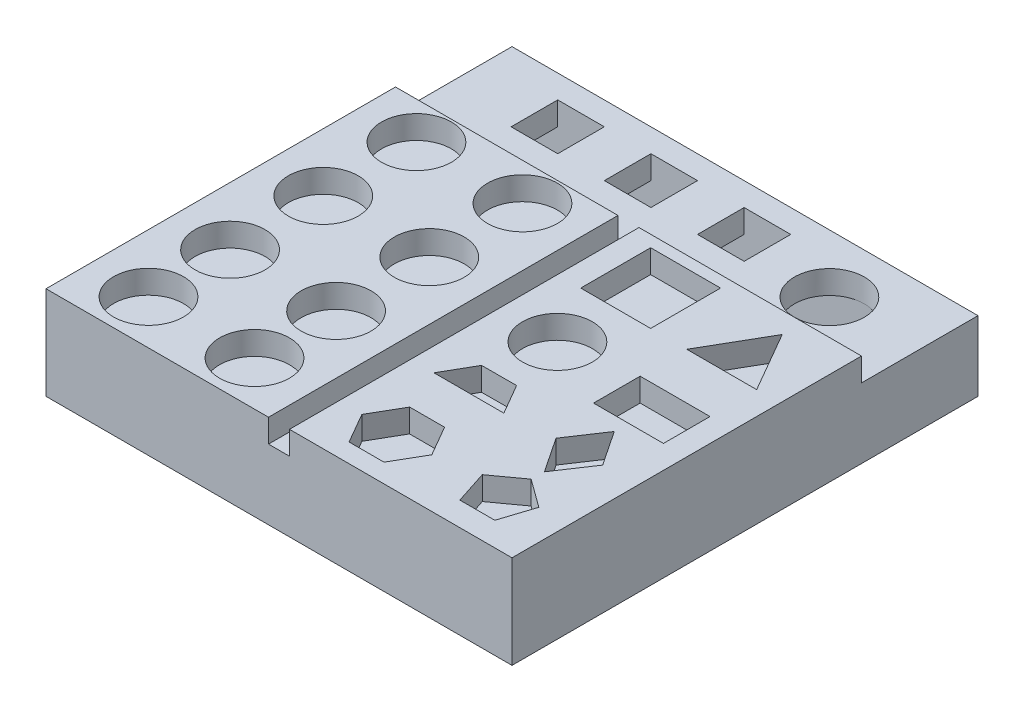
SolidWorks part; units mm, degrees
ref_plane "Alzado" through (0, 0, 0) normal (0, 0, 1) x (1, 0, 0)
ref_plane "Planta" through (0, 0, 0) normal (0, 1, 0) x (1, 0, 0)
ref_plane "Vista lateral" through (0, 0, 0) normal (1, 0, 0) x (0, 0, -1)
sketch "Croquis1" plane through (0, 0, 0) normal (0, 1, 0) x (1, 0, 0)
  line L1 (-200, 200) -> (0, 200)
  line L2 (-200, 200) -> (-200, 0)
  line L3 (-200, 0) -> (0, 0)
  line L4 (0, 200) -> (0, 0)
  dimension "D1" = 200
  dimension "D2" = 200
extrude "Saliente-Extruir1" add sketch "Croquis1" along normal blind 10 contours L2 L1 L4 L3
sketch "Croquis2" plane through (0, 10, 0) normal (0, 1, 0) x (1, 0, 0)
  line L0 (-200, 0) -> (0, 0) construction
  line L1 (-95.5, 0) -> (0, 0)
  line L2 (-95.5, 0) -> (-95.5, 150)
  line L3 (-95.5, 150) -> (0, 150)
  line L4 (0, 0) -> (0, 150)
  line L5 (0, 200) -> (0, 0) construction
  line L6 (-200, 200) -> (-200, 0) construction
  line L7 (-200, 150) -> (-104.5, 150)
  line L8 (-200, 150) -> (-200, 0)
  line L9 (-200, 0) -> (-104.5, 0)
  line L10 (-104.5, 150) -> (-104.5, 0)
  dimension "D1" = 95.5
  dimension "D2" = 150
  dimension "D3" = 95.5
  dimension "D4" = 150
extrude "Saliente-Extruir2" add sketch "Croquis2" along normal blind 10
sketch "Croquis3" plane through (0, 10, 0) normal (0, 1, 0) x (1, 0, 0)
  line L0 (-200, 200) -> (0, 200) construction
  line L1 (-170.376, 190) -> (-150.376, 190)
  line L2 (-170.376, 190) -> (-170.376, 170)
  line L3 (-170.376, 170) -> (-150.376, 170)
  line L4 (-150.376, 190) -> (-150.376, 170)
  line L5 (-170.376, 190) -> (-150.376, 170) construction
  line L6 (-170.376, 170) -> (-150.376, 190) construction
  line L7 (-130.376, 190) -> (-110.376, 190)
  line L8 (-130.376, 190) -> (-130.376, 170)
  line L9 (-130.376, 170) -> (-110.376, 170)
  line L10 (-110.376, 190) -> (-110.376, 170)
  line L11 (-130.376, 190) -> (-110.376, 170) construction
  line L12 (-130.376, 170) -> (-110.376, 190) construction
  line L13 (-90.376, 190) -> (-70.376, 190)
  line L14 (-90.376, 190) -> (-90.376, 170)
  line L15 (-90.376, 170) -> (-70.376, 170)
  line L16 (-70.376, 190) -> (-70.376, 170)
  line L17 (-90.376, 190) -> (-70.376, 170) construction
  line L18 (-90.376, 170) -> (-70.376, 190) construction
  circle A0 centre (-38.7808, 175) radius 15
  point P2 (-160.376, 180)
  point P7 (-120.376, 180)
  point P12 (-80.376, 180)
  dimension "D1" = 30
  dimension "D2" = 20
  dimension "D3" = 20
  dimension "D4" = 20
  dimension "D5" = 20
  dimension "D6" = 20
  dimension "D7" = 20
  dimension "D8" = 10
  dimension "D9" = 10
  dimension "D10" = 10
  dimension "D11" = 20
  dimension "D12" = 20
extrude "Cortar-Extruir1" cut sketch "Croquis3" against normal through all
sketch "Croquis4" plane through (0, 0, 0) normal (0, -1, 0) x (-1, 0, 0)
  line L0 (200, 200) -> (0, 200) construction
  line L1 (200, 0) -> (190, 0)
  line L2 (200, 0) -> (200, 200)
  line L3 (200, 200) -> (190, 200)
  line L4 (190, 0) -> (190, 200)
  line L5 (0, 200) -> (0, 0) construction
  line L6 (200, 200) -> (0, 200)
  line L7 (200, 200) -> (200, 190)
  line L8 (200, 190) -> (0, 190)
  line L9 (0, 200) -> (0, 190)
  line L10 (200, 0) -> (0, 0) construction
  line L11 (0, 200) -> (10, 200)
  line L12 (0, 200) -> (0, 0)
  line L13 (0, 0) -> (10, 0)
  line L14 (10, 200) -> (10, 0)
  line L16 (0, 0) -> (200, 0)
  line L17 (0, 0) -> (0, 10)
  line L18 (0, 10) -> (200, 10)
  line L19 (200, 0) -> (200, 10)
  dimension "D1" = 200
  dimension "D2" = 10
  dimension "D3" = 200
  dimension "D4" = 10
  dimension "D5" = 10
  dimension "D6" = 200
  dimension "D7" = 10
extrude "Saliente-Extruir3" add sketch "Croquis4" along normal blind 20 contours L17 L16 L19 L18 | L2 L1 L4 L3 | L7 L6 L9 L8 | L12 L11 L14 L13
sketch "Croquis6" plane through (0, -20, 0) normal (0, -1, 0) x (-1, 0, 0)
  line L0 (200, 0) -> (200, 200) construction
  line L1 (0, 0) -> (200, 0) construction
  line L2 (0, 0) -> (0, 200) construction
  line L3 (200, 200) -> (0, 200) construction
  circle A0 centre (195, 5) radius 2.5
  circle A1 centre (5, 5) radius 2.5
  circle A2 centre (5, 195) radius 2.5
  circle A3 centre (195, 195) radius 2.5
  dimension "D1" = 5
  dimension "D2" = 5
  dimension "D3" = 5
  dimension "D4" = 5
  dimension "D5" = 5
  dimension "D6" = 5
  dimension "D7" = 5
  dimension "D8" = 5
  dimension "D9" = 5
  dimension "D10" = 5
  dimension "D11" = 5
  dimension "D12" = 5
extrude "Cortar-Extruir2" cut sketch "Croquis6" against normal blind 15 contours A0 | A1 | A2 | A3
sketch "Croquis7" plane through (0, 20, 0) normal (0, 1, 0) x (1, 0, 0)
  line L0 (-200, 150) -> (-200, 0) construction
  line L1 (-104.5, 0) -> (-104.5, 150) construction
  line L2 (-104.5, 150) -> (-200, 150) construction
  line L3 (-200, 0) -> (-104.5, 0) construction
  circle A0 centre (-175, 134) radius 15
  circle A1 centre (-129.5, 134) radius 15
  circle A2 centre (-175, 94) radius 15
  circle A3 centre (-129.5, 94) radius 15
  circle A4 centre (-175, 54) radius 15
  circle A5 centre (-129.5, 54) radius 15
  circle A6 centre (-175, 19) radius 15
  circle A7 centre (-129.5, 19) radius 15
  dimension "D1" = 30
  dimension "D3" = 30
  dimension "D4" = 25
  dimension "D5" = 25
  dimension "D6" = 30
  dimension "D7" = 40
  dimension "D8" = 30
  dimension "D9" = 40
  dimension "D10" = 25
  dimension "D11" = 30
  dimension "D12" = 30
  dimension "D13" = 40
  dimension "D14" = 40
  dimension "D15" = 30
  dimension "D16" = 30
  dimension "D17" = 25
  dimension "D18" = 35
  dimension "D19" = 16
  dimension "D20" = 16
  dimension "D21" = 19
  dimension "D22" = 35
  dimension "D2" = 25
extrude "Cortar-Extruir3" cut sketch "Croquis7" against normal blind 10 contours A0 | A4 | A2 | A3 | A5 | A1 | A7 | A6
sketch "Croquis8" plane through (0, 20, 0) normal (0, 1, 0) x (1, 0, 0)
  line L0 (0, 150) -> (-95.5, 150) construction
  line L1 (-85.5, 145) -> (-55.5, 145)
  line L2 (-85.5, 145) -> (-85.5, 115)
  line L3 (-85.5, 115) -> (-55.5, 115)
  line L4 (-55.5, 145) -> (-55.5, 115)
  line L5 (-85.5, 145) -> (-55.5, 115) construction
  line L6 (-85.5, 115) -> (-55.5, 145) construction
  line L7 (-95.5, 150) -> (-95.5, 0) construction
  line L8 (-40, 115) -> (-10, 115)
  line L9 (-40, 115) -> (-25, 140.9808)
  line L10 (-25, 140.9808) -> (-10, 115)
  line L11 (0, 0) -> (0, 150) construction
  line L12 (-95.5, 150) -> (-95.5, 0) construction
  line L13 (-85.5, 52.0096) -> (-55.5, 52.0096)
  line L14 (-40, 95) -> (-10, 95)
  line L15 (-40, 95) -> (-40, 75)
  line L16 (-40, 75) -> (-10, 75)
  line L17 (-10, 95) -> (-10, 75)
  line L18 (-55.5, 52.0096) -> (-63.0492, 65.0169)
  line L19 (-63.0492, 65.0169) -> (-78.0491, 64.9828)
  line L20 (-78.0491, 64.9828) -> (-85.5, 52.0096)
  line L24 (-58.9445, 46.0804) -> (-55.2093, 52.584) [skipped]
  line L25 (-85.5196, 51.9754) -> (-81.7549, 45.4888) [skipped]
  line L26 (-77.9901, 39.0021) -> (-62.9902, 39.0362) [skipped]
  line L42 (-25, 68.896) -> (-35, 53.896)
  line L43 (-25, 38.9057) -> (-35, 53.896)
  line L44 (-15, 53.896) -> (-25, 68.896)
  line L45 (-25, 38.9057) -> (-15, 53.896)
  line L46 (-55.5, 21.0682) -> (-63, 34.0586)
  line L47 (-63, 34.0586) -> (-78, 34.0586)
  line L48 (-78, 34.0586) -> (-85.5, 21.0682)
  line L49 (-85.5, 21.0682) -> (-78, 8.0778)
  line L50 (-78, 8.0778) -> (-63, 8.0778)
  line L51 (-63, 8.0778) -> (-55.5, 21.0682)
  line L58 (-25.1353, 33.3389) -> (-37.2705, 24.5221)
  line L59 (-25.1353, 33.3389) -> (-13, 24.5221)
  line L60 (-37.2705, 24.5221) -> (-32.6353, 10.2563)
  line L61 (-32.6353, 10.2563) -> (-17.6353, 10.2563)
  line L62 (-17.6353, 10.2563) -> (-13, 24.5221)
  circle A0 centre (-70.5, 90) radius 15
  arc A1 (-59.2844, 58.5302) -> (-81.7844, 58.4791) centre (-70.5197, 52.0095) ccw construction
  circle A2 centre (-70.5, 21.0682) radius 12.9904 construction
  point P0 (-70.5, 130)
  point P51 (0, 0)
  dimension "D9" = 30
  dimension "D10" = 25
  dimension "D11" = 25
  dimension "D1" = 30
  dimension "D2" = 30
  dimension "D3" = 5
  dimension "D4" = 10
  dimension "D5" = 30
  dimension "D6" = 30
  dimension "D7" = 30
  dimension "D8" = 10
  dimension "D12" = 20
  dimension "D13" = 30
  dimension "D14" = 10
  dimension "D15" = 20
  dimension "D16" = 25
  dimension "D17" = 30
  dimension "D18" = 15
  dimension "D19" = 10
  dimension "D20" = 29.9903
  dimension "D21" = 30
  dimension "D22" = 10
  dimension "D23" = 15
  dimension "D24" = 15
  dimension "D25" = 108
  dimension "D26" = 25
  dimension "D27" = 108
  dimension "D28" = 108
  dimension "D29" = 108
  dimension "D30" = 15
  dimension "D31" = 15
  dimension "D32" = 15
  dimension "D33" = 13
  dimension "D34" = 14.2658
  dimension "D35" = 18.0278
extrude "Cortar-Extruir4" cut sketch "Croquis8" against normal blind 10 contours L2 L1 L4 L3 | L10 L8 L9 | L15 L14 L17 L16 | A0 | L46 L47 L48 L49 L50 L51 | L13 L18 L19 L20 | L45 L44 L42 L43 | L62 L59 L58 L60 L61
